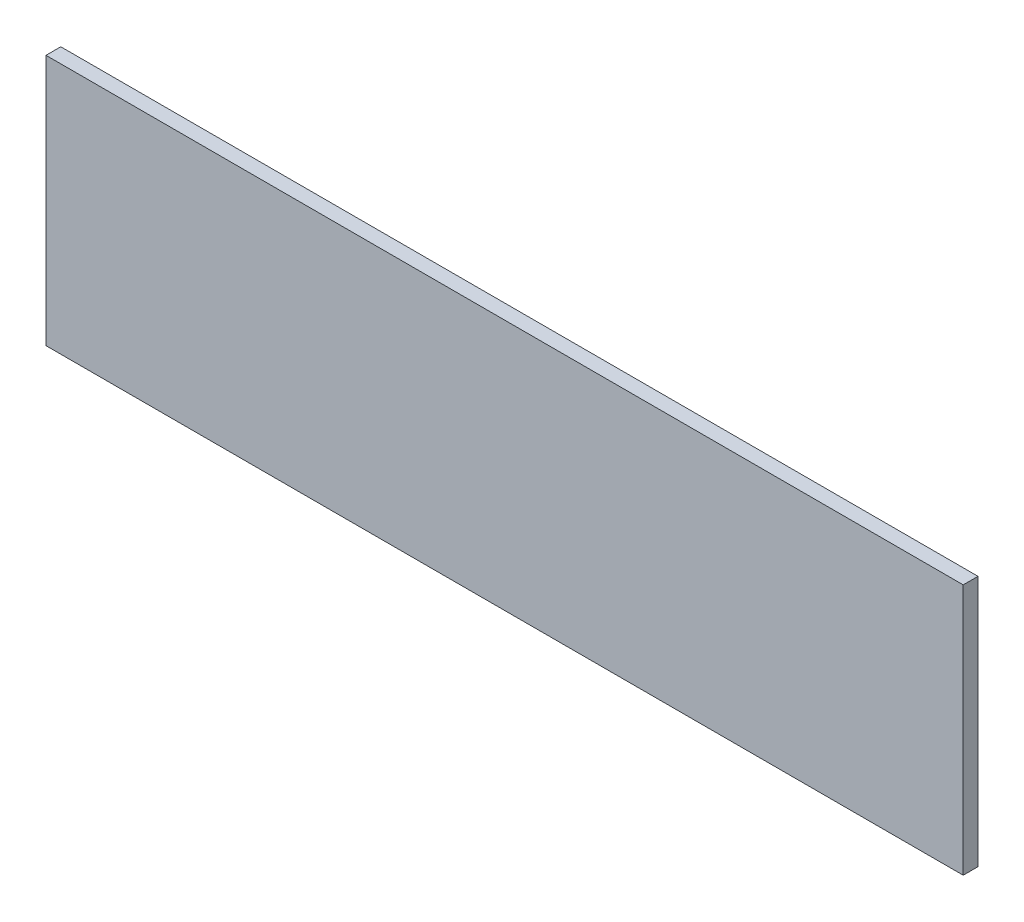
SolidWorks part; units mm, degrees
ref_plane "Front Plane" through (0, 0, 0) normal (0, 0, 1) x (1, 0, 0)
ref_plane "Top Plane" through (0, 0, 0) normal (0, 1, 0) x (1, 0, 0)
ref_plane "Right Plane" through (0, 0, 0) normal (1, 0, 0) x (0, 0, -1)
sketch "Sketch1" plane through (0, 0, 0) normal (0, 0, 1) x (1, 0, 0)
  line L2 (-62, -17) -> (62, -17)
  line L3 (-62, -17) -> (-62, 17)
  line L4 (-62, 17) -> (62, 17)
  line L5 (62, -17) -> (62, 17)
  line L6 (-62, -17) -> (62, 17) construction
  line L7 (-62, 17) -> (62, -17) construction
  point P2 (0, 0)
  dimension "D1" = 124
  dimension "D2" = 34
extrude "Boss-Extrude1" add sketch "Sketch1" along normal blind 2
